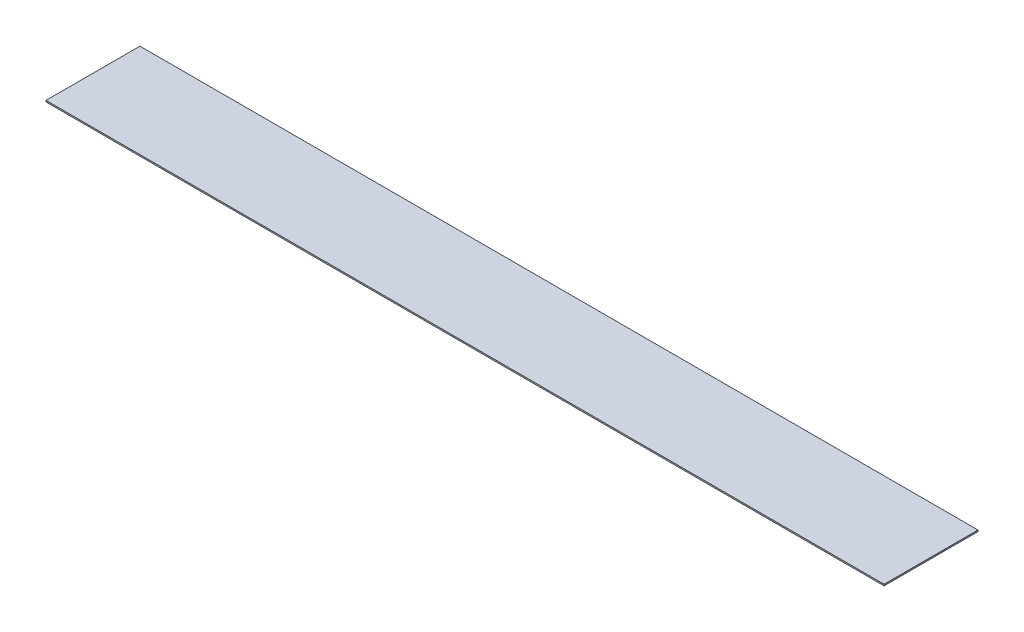
SolidWorks part; units mm, degrees
ref_plane "Front Plane" through (0, 0, 0) normal (0, 0, 1) x (1, 0, 0)
ref_plane "Top Plane" through (0, 0, 0) normal (0, 1, 0) x (1, 0, 0)
ref_plane "Right Plane" through (0, 0, 0) normal (1, 0, 0) x (0, 0, -1)
sketch "Sketch1" plane through (0, 0, 0) normal (0, 1, 0) x (1, 0, 0)
  line L1 (0, 0) -> (1785, 0)
  line L2 (0, 0) -> (0, 200)
  line L3 (0, 200) -> (1785, 200)
  line L4 (1785, 0) -> (1785, 200)
  dimension "D1" = 1785
  dimension "D2" = 200
extrude "Boss-Extrude1" add sketch "Sketch1" along normal blind 3
equation "\"boxWidth\"=1930.0"
equation "\"D1@Sketch1\"=\"boxWidth\"-70-70-5"
equation "\"start\"=700.0"
equation "\"CarBeamWidth\"=700.0"
equation "\"WheelWidth\"=650.0"
equation "\"Wheel_FrontBoxDistance\"=1390.0"
equation "\"boxLength\"=5100.0"
equation "\"MetalSheet_3mm_length\"=5030.0"
equation "\"MetalSheet_3mm_width\"=1923.0"
equation "\"MetalSheet_3mm_FloorCut_L_length\"=1764.0"
equation "\"MetalSheet_3mm_FloorCut_L_disdance\"=1665.0"
equation "\"MetalSheet_3mm_FloorCut_R_length\"=1764.0"
equation "\"MetalSheet_3mm_FloorCut_R_disdance\"=1665.0"
equation "\"indoorHeight\"=1940.0"
equation "\"indoorHeight_para\"=25.0"
equation "\"rearLightHeight_para\"=265.0"
equation "\"doorColumnBar_A_FR_3mm_length_Cut\"=2310.0"
equation "\"A\"=0.0"
equation "\"haveDoor_R\"=1"
equation "\"side_door_bottom_R_3mm_length\"=1934.0"
equation "\"side_door_bottom_R_3mm_toFrontDistance\"=1583.0"
equation "\"1Bar_Side_RF_3mm_length\"=1493.0"
equation "\"1Bar_Side_RB_3mm_length\"=1493.0"
equation "\"DoorSeparator_RF_3mm_withHinge_toFrontDistance\"=1673.0"
equation "\"DoorSeparator_RF_3mm_withHinge_exist\"=1"
equation "\"DoorSeparator_RB_3mm_withHinge_toFrontDistance\"=3427.0"
equation "\"DoorSeparator_RB_3mm_withHinge_exist\"=1"
equation "\"Door_R1_L_open_Single_toFrontDistance\"=2547.5"
equation "\"Door_R1_L_open_Single_exist\"=1"
equation "\"door_base_long7_R1_L_open_Single_height\"=1890.0"
equation "\"door_base_short7_R1_L_open_Single_height\"=1890.0"
equation "\"door_base_short7_R1_L_open_Single_width\"=864"
equation "\"Door_R1_R_open_Single_toFrontDistance\"=3422.0"
equation "\"Door_R1_R_open_Single_exist\"=1"
equation "\"door_base_long7_R1_R_open_Single_height\"=1890.0"
equation "\"door_base_short7_R1_R_open_Single_height\"=1890.0"
equation "\"door_base_short7_R1_R_open_Single_width\"=864"
equation "\"x\"=66.0"
equation "\"door_base_double_BL_height\"=1890.0"
equation "\"door_base_short7_BL_Single_height\"=1890.0"
equation "\"door_base_short7_BL_Single_width\"=864"
equation "\"door_base_long7_BR_Single_height\"=1890.0"
equation "\"door_base_short7_BR_Single_height\"=1890.0"
equation "\"door_base_short7_BR_Single_width\"=864"
equation "\"da\"=62.0"
equation "\"SquareTube_length\"=1923.0"
equation "\"channelSteel_length\"=5030.0"
equation "\"SquareTube_inFront_AvgDistance\"=285.0"
equation "\"SquareTube_inFront_TotalCount\"=5"
equation "\"SquareTube_inFront1_cutDepth50_R\"=0.5"
equation "\"SquareTube_inFront1_cutDepth50_L\"=0.5"
equation "\"SquareTube_inFront2_cutDepth50_R\"=0.5"
equation "\"SquareTube_inFront2_cutDepth50_L\"=0.5"
equation "\"SquareTube_inFront3_cutDepth50_R\"=0.5"
equation "\"SquareTube_inFront3_cutDepth50_L\"=0.5"
equation "\"SquareTube_inFront4_cutDepth50_R\"=0.5"
equation "\"SquareTube_inFront4_cutDepth50_L\"=0.5"
equation "\"SquareTube_inFront5_cutDepth50_R\"=50"
equation "\"SquareTube_inFront5_cutDepth50_L\"=50"
equation "\"SquareTube_inFront6_cutDepth50_R\"=50"
equation "\"SquareTube_inFront6_cutDepth50_L\"=50"
equation "\"SquareTube_inFront7_cutDepth50_R\"=50"
equation "\"SquareTube_inFront7_cutDepth50_L\"=50"
equation "\"SquareTube_inFront8_cutDepth50_R\"=50"
equation "\"SquareTube_inFront8_cutDepth50_L\"=50"
equation "\"SquareTube_inFront9_cutDepth50_R\"=50"
equation "\"SquareTube_inFront9_cutDepth50_L\"=50"
equation "\"SquareTube_inFront10_cutDepth50_R\"=50"
equation "\"SquareTube_inFront10_cutDepth50_L\"=50"
equation "\"SquareTube_inFront11_cutDepth50_R\"=50"
equation "\"SquareTube_inFront11_cutDepth50_L\"=50"
equation "\"SquareTube_inFront12_cutDepth50_R\"=50"
equation "\"SquareTube_inFront12_cutDepth50_L\"=50"
equation "\"SquareTube_inFront13_cutDepth50_R\"=50"
equation "\"SquareTube_inFront13_cutDepth50_L\"=50"
equation "\"SquareTube_inFront14_cutDepth50_R\"=50"
equation "\"SquareTube_inFront14_cutDepth50_L\"=50"
equation "\"SquareTube_inBack_AvgDistance\"=333.125"
equation "\"SquareTube_inBack_TotalCount\"=9"
equation "\"SquareTube_inBack1_cutDepth50_R\"=50"
equation "\"SquareTube_inBack1_cutDepth50_L\"=50"
equation "\"SquareTube_inBack2_cutDepth50_R\"=50"
equation "\"SquareTube_inBack2_cutDepth50_L\"=50"
equation "\"SquareTube_inBack3_cutDepth50_R\"=50"
equation "\"SquareTube_inBack3_cutDepth50_L\"=50"
equation "\"SquareTube_inBack4_cutDepth50_R\"=50"
equation "\"SquareTube_inBack4_cutDepth50_L\"=50"
equation "\"SquareTube_inBack5_cutDepth50_R\"=50"
equation "\"SquareTube_inBack5_cutDepth50_L\"=50"
equation "\"SquareTube_inBack6_cutDepth50_R\"=0.5"
equation "\"SquareTube_inBack6_cutDepth50_L\"=0.5"
equation "\"SquareTube_inBack7_cutDepth50_R\"=0.5"
equation "\"SquareTube_inBack7_cutDepth50_L\"=0.5"
equation "\"SquareTube_inBack8_cutDepth50_R\"=0.5"
equation "\"SquareTube_inBack8_cutDepth50_L\"=0.5"
equation "\"doorColumnBar_A_FL_3mm_length_Cut\"=2310.0"
equation "\"B\"=0.0"
equation "\"haveDoor_L\"=1"
equation "\"side_door_bottom_L_3mm_length\"=1934.0"
equation "\"side_door_bottom_L_3mm_toFrontDistance\"=1583.0"
equation "\"1Bar_Side_LF_3mm_length\"=1493.0"
equation "\"1Bar_Side_LB_3mm_length\"=1493.0"
equation "\"DoorSeparator_LF_3mm_withHinge_toFrontDistance\"=1673.0"
equation "\"DoorSeparator_LF_3mm_withHinge_exist\"=1"
equation "\"DoorSeparator_LB_3mm_withHinge_toFrontDistance\"=3427.0"
equation "\"DoorSeparator_LB_3mm_withHinge_exist\"=1"
equation "\"Door_L1_L_open_Single_toFrontDistance\"=3422.0"
equation "\"Door_L1_L_open_Single_exist\"=1"
equation "\"door_base_long7_L1_L_open_Single_height\"=1890.0"
equation "\"door_base_short7_L1_L_open_Single_height\"=1890.0"
equation "\"door_base_short7_L1_L_open_Single_width\"=864"
equation "\"Door_L1_R_open_Single_toFrontDistance\"=2547.5"
equation "\"Door_L1_R_open_Single_exist\"=1"
equation "\"door_base_long7_L1_R_open_Single_height\"=1890.0"
equation "\"door_base_short7_L1_R_open_Single_height\"=1890.0"
equation "\"door_base_short7_L1_R_open_Single_width\"=864"
